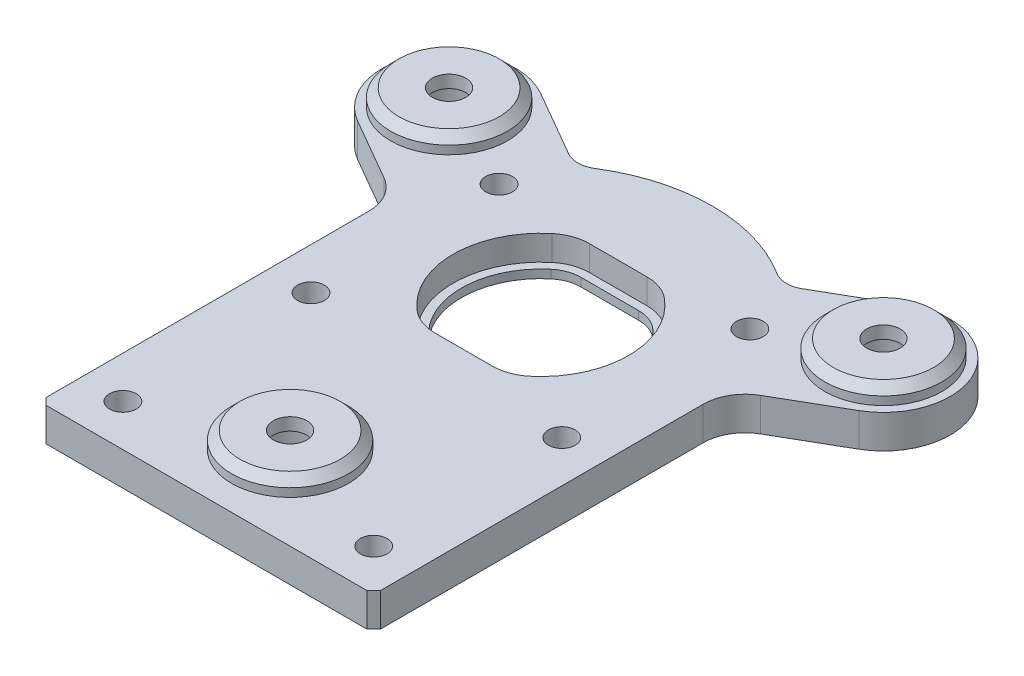
SolidWorks part; units mm, degrees
ref_plane "Front Plane" through (0, 0, 0) normal (0, 0, 1) x (1, 0, 0)
ref_plane "Top Plane" through (0, 0, 0) normal (0, 1, 0) x (1, 0, 0)
ref_plane "Right Plane" through (0, 0, 0) normal (1, 0, 0) x (0, 0, -1)
ref_plane "Plane1" through (0, 4, 0) normal (0, 1, 0) x (1, 0, 0)
sketch "Sketch1" plane through (0, 4, 0) normal (0, 1, 0) x (1, 0, 0)
  line L0 (20, -17) -> (20, 25.3094)
  line L1 (20, 25.3094) -> (29.9808, 31.0718)
  line L2 (21.9808, 44.9282) -> (12.3459, 39.3655)
  line L3 (-12.3459, 39.3655) -> (-21.9808, 44.9282)
  line L4 (-29.9808, 31.0718) -> (-20, 25.3094)
  line L5 (-20, 25.3094) -> (-20, -17)
  line L6 (-20, -17) -> (20, -17)
  arc A0 (29.9808, 31.0718) -> (21.9808, 44.9282) centre (25.9808, 38) ccw
  arc A1 (12.3459, 39.3655) -> (-12.3459, 39.3655) centre (0, 23) ccw
  arc A2 (-21.9808, 44.9282) -> (-29.9808, 31.0718) centre (-25.9808, 38) ccw
extrude "Boss-Extrude1" add sketch "Sketch1" against normal blind 4
sketch "Sketch2" plane through (0, 4, 0) normal (0, 1, 0) x (-1, 0, 0)
  line L0 (-4.9687, -32.25) -> (4.9687, -32.25)
  line L1 (4.9687, -13.75) -> (-4.9687, -13.75)
  arc A0 (4.9687, -32.25) -> (4.9687, -13.75) centre (0, -23) ccw
  arc A1 (-4.9687, -13.75) -> (-4.9687, -32.25) centre (0, -23) ccw
extrude "Cut-Extrude1" cut sketch "Sketch2" against normal blind 3
sketch "Sketch3" plane through (0, 0, 0) normal (0, -1, 0) x (1, 0, 0)
  line L0 (4.7104, -14.75) -> (-4.7104, -14.75)
  line L1 (-4.7104, -31.25) -> (4.7104, -31.25)
  arc A0 (-4.7104, -14.75) -> (-4.7104, -31.25) centre (0, -23) ccw
  arc A1 (4.7104, -31.25) -> (4.7104, -14.75) centre (0, -23) ccw
extrude "Cut-Extrude2" cut sketch "Sketch3" against normal through all
ref_plane "Plane2" through (0, 0, -38) normal (0, 0, -1) x (-1, 0, 0)
sketch "Sketch4" plane through (0, 0, -38) normal (0, 0, -1) x (-1, 0, 0)
  line L0 (18.9808, 4) -> (25.9808, 4)
  line L1 (25.9808, 4) -> (25.9808, 6)
  line L2 (25.9808, 6) -> (19.9808, 6)
  line L3 (19.9808, 6) -> (18.9808, 5)
  line L4 (18.9808, 5) -> (18.9808, 4)
  line L5 (25.9808, 4) -> (25.9808, 6) construction
revolve "Revolve1" add sketch "Sketch4" angle 360 about L5
ref_plane "Plane3" through (0, 0, 7) normal (0, 0, -1) x (-1, 0, 0)
sketch "Sketch5" plane through (0, 0, 7) normal (0, 0, -1) x (-1, 0, 0)
  line L0 (-7, 4) -> (0, 4)
  line L1 (0, 4) -> (0, 6)
  line L2 (0, 6) -> (-6, 6)
  line L3 (-6, 6) -> (-7, 5)
  line L4 (-7, 5) -> (-7, 4)
  line L5 (0, 4) -> (0, 6) construction
revolve "Revolve2" add sketch "Sketch5" angle 360 about L5
sketch "Sketch6" plane through (0, 0, -38) normal (0, 0, -1) x (-1, 0, 0)
  line L0 (-32.9808, 4) -> (-25.9808, 4)
  line L1 (-25.9808, 4) -> (-25.9808, 6)
  line L2 (-25.9808, 6) -> (-31.9808, 6)
  line L3 (-31.9808, 6) -> (-32.9808, 5)
  line L4 (-32.9808, 5) -> (-32.9808, 4)
  line L5 (-25.9808, 4) -> (-25.9808, 6) construction
revolve "Revolve3" add sketch "Sketch6" angle 360 about L5
hole_wizard "Ø3.2 (3.2) Diameter Hole1" positions "Sketch8" profile "Sketch7" hole size "Ø3.2" standard "ANSI Metric"
sketch "Sketch8" plane through (0, 0, 0) normal (0, -1, 0) x (-1, 0, 0)
  point P0 (15, 33)
  point P1 (-15, 10.5)
  point P2 (15, -12)
  point P3 (-15, -12)
  point P4 (15, 10.5)
  point P5 (-15, 33)
sketch "Sketch7" plane through (-15, 0, -33) normal (1, 0, 0) x (0, 0, -1)
  line L0 (0, 0) -> (0, 6)
  line L1 (0, 6) -> (1.6, 6)
  line L2 (1.6, 6) -> (1.6, 0)
  line L5 (1.6, 0) -> (0, 0)
  line L11 (0, -6.35) -> (0, 107.95) construction
  dimension "Thru Hole Dia." = 3.2
  dimension "Thru Hole Depth" = 6
hole_wizard "CBORE for M3.5 Hex Head Machine Screw1" positions "Sketch10" profile "Sketch9" counterbore size "M3.5" standard "ANSI Metric"
sketch "Sketch10" plane through (0, 0, 0) normal (0, -1, 0) x (-1, 0, 0)
  point P0 (0, -7)
  point P1 (-25.9808, 38)
  point P2 (25.9808, 38)
sketch "Sketch9" plane through (0, 0, 7) normal (1, 0, 0) x (0, 0, -1)
  line L0 (0, 0) -> (0, 6)
  line L1 (0, 6) -> (2, 6)
  line L3 (2, 6) -> (2, 4.5)
  line L4 (2, 4.5) -> (4, 4.5)
  line L5 (4, 4.5) -> (4, 0)
  line L7 (4, 0) -> (0, 0)
  line L11 (0, -6.35) -> (0, 107.95) construction
  dimension "Thru Hole Dia." = 4
  dimension "Thru Hole Depth" = 6
  dimension "C'Bore Dia." = 8
  dimension "C'Bore Depth" = 4.5
chamfer "Chamfer1" distance 1.55 angle 45 6 edges at (-15, 0, -12.1) (15, 0, 10.4) (15, 0, -34.6) (-15, 0, -34.6) (-15, 0, 10.4) (15, 0, -12.1)
chamfer "Chamfer2" distance 0.8 angle 45 1 edges at (-20, 2, 17)
chamfer "Chamfer3" distance 0.8 angle 45 1 edges at (20, 2, 17)
fillet "Fillet1" radius 3 2 edges at (12.3459, 2, -39.3655) (-12.3459, 2, -39.3655)
fillet "Fillet2" radius 4.1 4 edges at (-4.7104, 0.5, -14.75) (-4.7104, 0.5, -31.25) (4.7104, 0.5, -14.75) (4.7104, 0.5, -31.25)
fillet "Fillet3" radius 5 2 edges at (-20, 2, -25.3094) (20, 2, -25.3094)
fillet "Fillet4" radius 5.1 4 edges at (-4.9687, 2.5, -13.75) (-4.9687, 2.5, -32.25) (4.9687, 2.5, -13.75) (4.9687, 2.5, -32.25)
